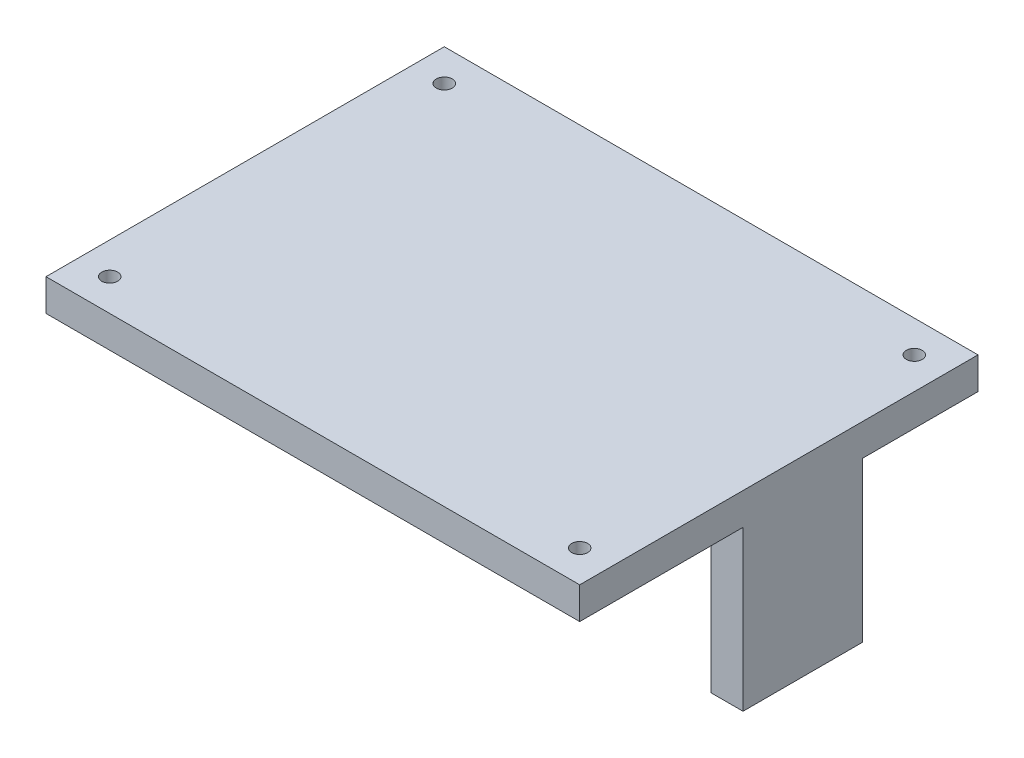
SolidWorks part; units mm, degrees
ref_plane "Front Plane" through (0, 0, 0) normal (0, 0, 1) x (1, 0, 0)
ref_plane "Top Plane" through (0, 0, 0) normal (0, 1, 0) x (1, 0, 0)
ref_plane "Right Plane" through (0, 0, 0) normal (1, 0, 0) x (0, 0, -1)
sketch "Sketch1" plane through (0, 9.8688, 0) normal (0, 1, 0) x (1, 0, 0)
  line L0 (40.7444, 16.3739) -> (40.7444, 8.3739)
  line L20 (38.7444, 8.3739) -> (38.7444, 2.3739)
  line L21 (38.7444, 2.3739) -> (36.7444, 2.3739)
  line L22 (36.7444, 2.3739) -> (36.7444, 0.3739)
  line L23 (36.7444, 0.3739) -> (11.2444, 0.3739)
  line L24 (11.2444, 0.3739) -> (11.2444, 2.3739)
  line L25 (11.2444, 2.3739) -> (9.2444, 2.3739)
  line L26 (9.2444, 2.3739) -> (9.2444, 19.3739)
  line L27 (9.2444, 19.3739) -> (11.2444, 19.3739)
  line L28 (11.2444, 19.3739) -> (11.2444, 21.3739)
  line L29 (11.2444, 21.3739) -> (36.7444, 21.3739)
  line L30 (36.7444, 21.3739) -> (36.7444, 19.3739)
  line L31 (36.7444, 19.3739) -> (38.7444, 19.3739)
  line L32 (38.7444, 19.3739) -> (38.7444, 16.3739)
  line L33 (38.7444, 16.3739) -> (40.7444, 16.3739)
  line L34 (40.7444, 16.3739) -> (40.7444, 23.3739)
  line L35 (40.7444, 23.3739) -> (7.2444, 23.3739)
  line L36 (7.2444, 23.3739) -> (7.2444, -1.6261)
  line L37 (7.2444, -1.6261) -> (40.7444, -1.6261)
  line L38 (40.7444, -1.6261) -> (40.7444, 8.3739)
  line L39 (40.7444, 8.3739) -> (38.7444, 8.3739)
  line L40 (38.7444, 8.3739) -> (38.7444, 2.3739)
  line L41 (38.7444, 2.3739) -> (36.7444, 2.3739)
  line L42 (36.7444, 2.3739) -> (36.7444, 0.3739)
  line L43 (36.7444, 0.3739) -> (11.2444, 0.3739)
  line L44 (11.2444, 0.3739) -> (11.2444, 2.3739)
  line L45 (11.2444, 2.3739) -> (9.2444, 2.3739)
  line L46 (9.2444, 2.3739) -> (9.2444, 19.3739)
  line L47 (9.2444, 19.3739) -> (11.2444, 19.3739)
  line L48 (11.2444, 19.3739) -> (11.2444, 21.3739)
  line L49 (11.2444, 21.3739) -> (36.7444, 21.3739)
  line L50 (36.7444, 21.3739) -> (36.7444, 19.3739)
  line L51 (36.7444, 19.3739) -> (38.7444, 19.3739)
  line L52 (38.7444, 19.3739) -> (38.7444, 16.3739)
  line L53 (38.7444, 16.3739) -> (40.7444, 16.3739)
  line L54 (40.7444, 16.3739) -> (40.7444, 23.3739)
  line L55 (40.7444, 23.3739) -> (7.2444, 23.3739)
  line L56 (7.2444, 23.3739) -> (7.2444, -1.6261)
  line L57 (7.2444, -1.6261) -> (40.7444, -1.6261)
  line L58 (40.7444, -1.6261) -> (40.7444, 8.3739)
  line L59 (40.7444, 8.3739) -> (38.7444, 8.3739)
  circle A0 centre (38.7444, 21.3739) radius 0.5 construction
  circle A1 centre (38.7444, 0.3739) radius 0.5 construction
  circle A2 centre (9.2444, 0.3739) radius 0.5 construction
  circle A3 centre (9.2444, 21.3739) radius 0.5 construction
  circle A4 centre (38.7444, 21.3739) radius 0.5
  circle A5 centre (38.7444, 0.3739) radius 0.5
  circle A6 centre (9.2444, 0.3739) radius 0.5
  circle A7 centre (9.2444, 21.3739) radius 0.5
  circle M21 centre (9.2444, 0.3739) radius 0.5
  circle M22 centre (9.2444, 21.3739) radius 0.5
  circle M23 centre (38.7444, 21.3739) radius 0.5
  circle M24 centre (38.7444, 0.3739) radius 0.5
  line M25 (38.7444, 8.3739) -> (38.7444, 2.3739)
  line M26 (38.7444, 2.3739) -> (36.7444, 2.3739)
  line M27 (36.7444, 2.3739) -> (36.7444, 0.3739)
  line M28 (36.7444, 0.3739) -> (11.2444, 0.3739)
  line M29 (11.2444, 0.3739) -> (11.2444, 2.3739)
  line M30 (11.2444, 2.3739) -> (9.2444, 2.3739)
  line M31 (9.2444, 2.3739) -> (9.2444, 19.3739)
  line M32 (9.2444, 19.3739) -> (11.2444, 19.3739)
  line M33 (11.2444, 19.3739) -> (11.2444, 21.3739)
  line M34 (11.2444, 21.3739) -> (36.7444, 21.3739)
  line M35 (36.7444, 21.3739) -> (36.7444, 19.3739)
  line M36 (36.7444, 19.3739) -> (38.7444, 19.3739)
  line M37 (38.7444, 19.3739) -> (38.7444, 16.3739)
  line M38 (38.7444, 16.3739) -> (40.7444, 16.3739)
  line M39 (40.7444, 16.3739) -> (40.7444, 23.3739)
  line M40 (40.7444, 23.3739) -> (7.2444, 23.3739)
  line M41 (7.2444, 23.3739) -> (7.2444, -1.6261)
  line M42 (7.2444, -1.6261) -> (40.7444, -1.6261)
  line M43 (40.7444, -1.6261) -> (40.7444, 8.3739)
  line M44 (40.7444, 8.3739) -> (38.7444, 8.3739)
  dimension "D1" = 0
extrude "Boss-Extrude1" add sketch "Sketch1" along normal blind 2 contours L0 M38 M37 M36 M35 M34 M33 M32 M31 M30 M29 M28 M27 M26 M25 M44 | M44 M25 M26 M27 M28 M29 M30 M31 M32 M33 M34 M35 M36 M37 M38 M39 M40 M41 M42 M43 M22 M24 M23 M21
sketch "Sketch2" plane through (0, 9.8688, 0) normal (0, -1, 0) x (1, 0, 0)
  line L0 (40.7444, -23.3739) -> (40.7444, 1.6261) construction
  line L1 (40.7444, -8.6239) -> (38.7444, -8.6239)
  line L2 (40.7444, -8.6239) -> (40.7444, -16.1239)
  line L3 (40.7444, -16.1239) -> (38.7444, -16.1239)
  line L4 (38.7444, -8.6239) -> (38.7444, -16.1239)
  dimension "D1" = 2
  dimension "D2" = 0.25
  dimension "D3" = 0.25
extrude "Boss-Extrude2" add sketch "Sketch2" along normal blind 10
